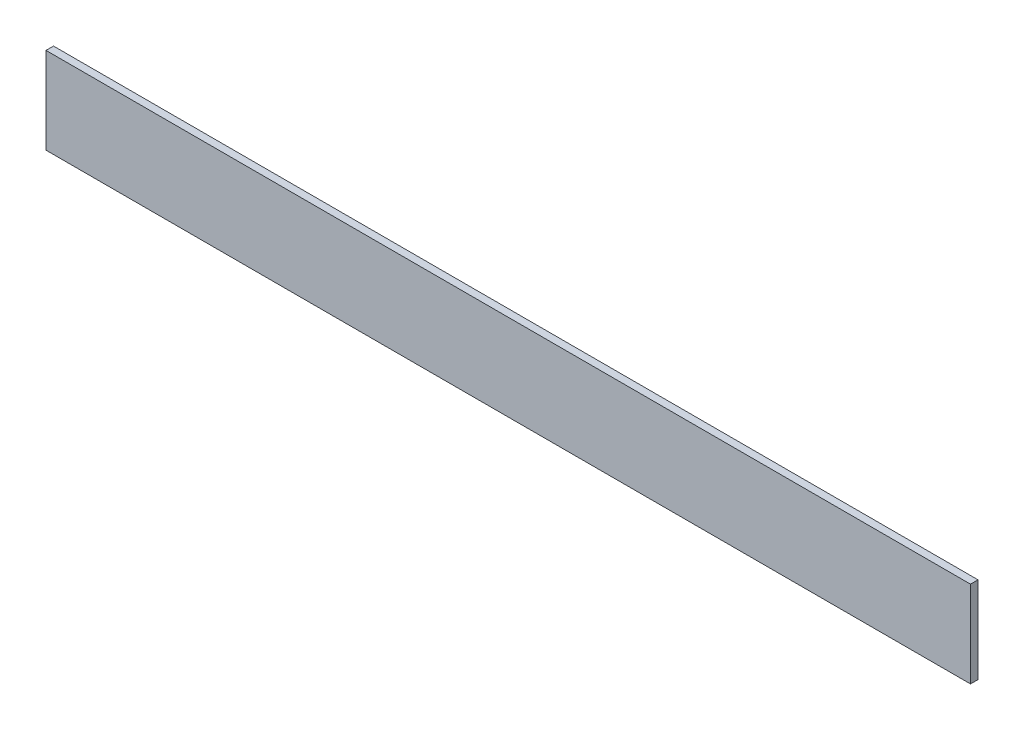
SolidWorks part; units mm, degrees
ref_plane "Front Plane" through (0, 0, 0) normal (0, 0, 1) x (1, 0, 0)
ref_plane "Top Plane" through (0, 0, 0) normal (0, 1, 0) x (1, 0, 0)
ref_plane "Right Plane" through (0, 0, 0) normal (1, 0, 0) x (0, 0, -1)
sketch "Sketch1" plane through (0, 0, 0) normal (0, 0, 1) x (1, 0, 0)
  line L0 (1230, 115) -> (1230, 0)
  line L1 (1230, 115) -> (0, 115)
  line L2 (1230, 0) -> (0, 0)
  line L3 (0, 115) -> (0, 0)
other "Pen Sketch1" parameters "D1"=69.7562, "D2"=44.2015
extrude "Boss-Extrude1" add sketch "Sketch1" along normal blind 10
